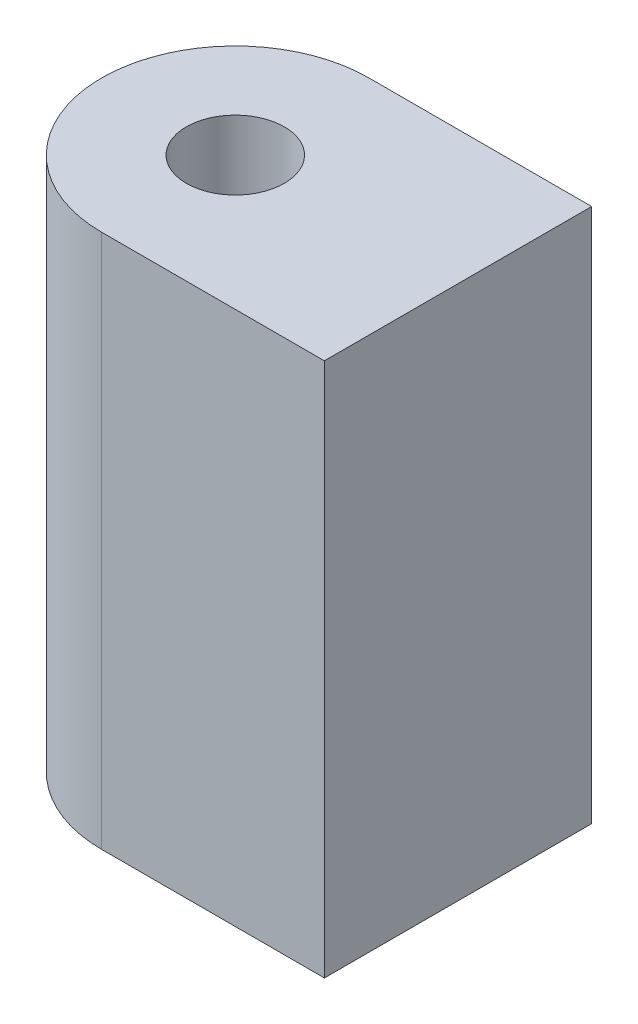
SolidWorks part; units mm, degrees
ref_plane "Front Plane" through (0, 0, 0) normal (0, 0, 1) x (1, 0, 0)
ref_plane "Top Plane" through (0, 0, 0) normal (0, 1, 0) x (1, 0, 0)
ref_plane "Right Plane" through (0, 0, 0) normal (1, 0, 0) x (0, 0, -1)
sketch "Sketch1" plane through (0, 0, 0) normal (0, 1, 0) x (1, 0, 0)
  line L1 (0, 7.5) -> (-12.5, 7.5)
  line L2 (0, 7.5) -> (0, -7.5)
  line L3 (0, -7.5) -> (-12.5, -7.5)
  arc A0 (-12.5, -7.5) -> (-12.5, 7.5) centre (-12.5, 0) cw
  circle A1 centre (-12.5, 0) radius 2.75
  point P4 (0, 0)
  point P6 (-20, 0)
  dimension "D2" = 5.5
  dimension "D1" = 20
  dimension "D3" = 15
extrude "Boss-Extrude1" add sketch "Sketch1" along normal blind 30
